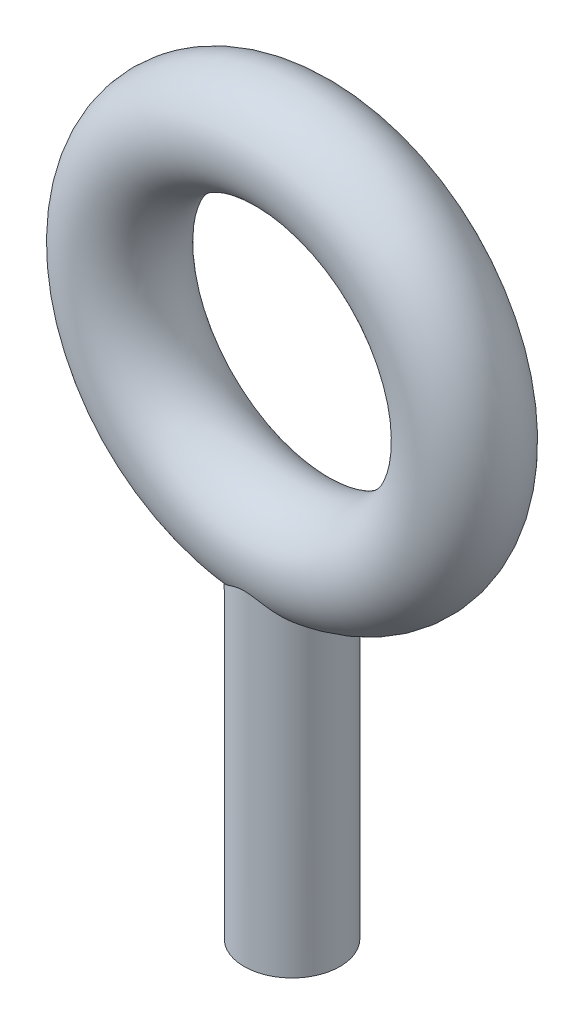
SolidWorks part; units mm, degrees
material "Tin Bearing Bronze"
ref_plane "Front Plane" through (0, 0, 0) normal (0, 0, 1) x (1, 0, 0)
ref_plane "Top Plane" through (0, 0, 0) normal (0, 1, 0) x (1, 0, 0)
ref_plane "Right Plane" through (0, 0, 0) normal (1, 0, 0) x (0, 0, -1)
sketch "Sketch1" plane through (0, 0, 0) normal (1, 0, 0) x (0, 0, -1)
  line L0 (0, 0) -> (21.8491, 0) construction
  circle A0 centre (0, -15.875) radius 4.7625
revolve "Revolve2" add sketch "Sketch1" angle 360 about L0
ref_plane "Plane2" through (0, -15.875, 0) normal (0, 1, 0) x (1, 0, 0)
sketch "Sketch2" plane through (0, -15.875, 0) normal (0, 1, 0) x (1, 0, 0)
  circle A0 centre (0, 0) radius 4.4132
extrude "Boss-Extrude1" add sketch "Sketch2" against normal blind 31.75
